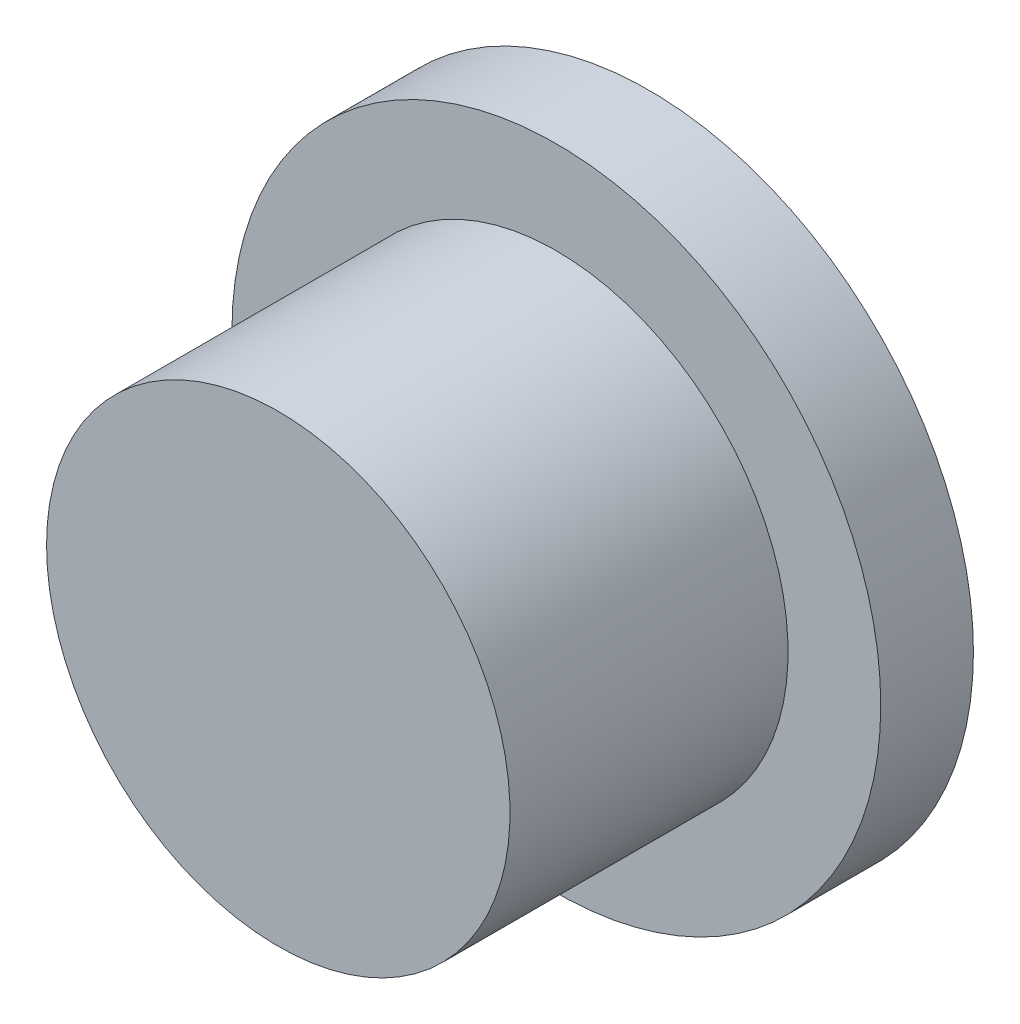
SolidWorks part; units mm, degrees
ref_plane "Front" through (0, 0, 0) normal (0, 0, 1) x (1, 0, 0)
ref_plane "Top" through (0, 0, 0) normal (0, 1, 0) x (1, 0, 0)
ref_plane "Right" through (0, 0, 0) normal (1, 0, 0) x (0, 0, -1)
sketch "Sketch2" plane through (0, 0, 0) normal (0, 0, 1) x (1, 0, 0)
  circle A0 centre (0, 0) radius 8.89
  dimension "D1" = 17.78
extrude "Boss-Extrude1" add sketch "Sketch2" along normal blind 2.54
sketch "Sketch3" plane through (0, 0, 2.54) normal (0, 0, 1) x (1, 0, 0)
  circle A0 centre (0, 0) radius 6.35
  dimension "D1" = 12.7
extrude "Boss-Extrude2" add sketch "Sketch3" along normal blind 7.62
